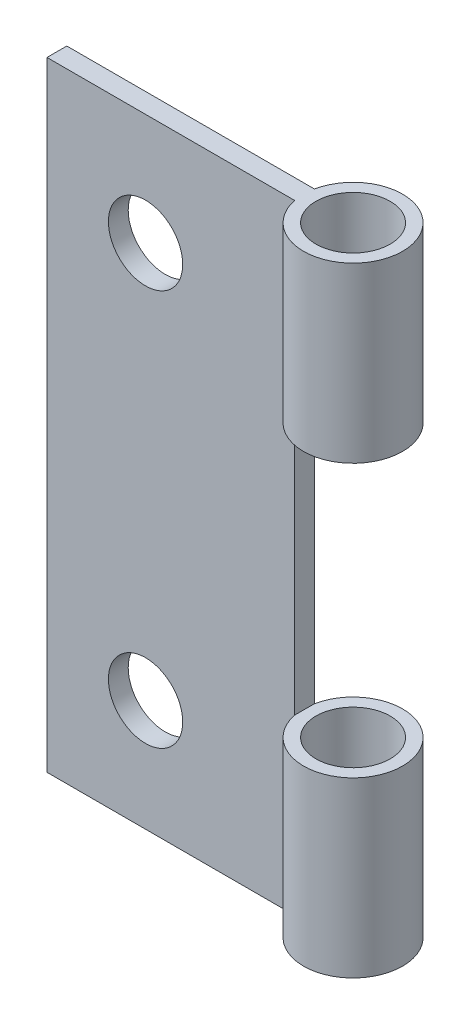
SolidWorks part; units mm, degrees
ref_plane "前视基准面" through (0, 0, 0) normal (0, 0, 1) x (1, 0, 0)
ref_plane "上视基准面" through (0, 0, 0) normal (0, 1, 0) x (1, 0, 0)
ref_plane "右视基准面" through (0, 0, 0) normal (1, 0, 0) x (0, 0, -1)
other "Configuration Table"
sketch "草图1" plane through (0, 0, 0) normal (0, 0, 1) x (1, 0, 0)
  line L1 (-5, -12.5) -> (5, -12.5)
  line L2 (-5, -12.5) -> (-5, 12.5)
  line L3 (-5, 12.5) -> (5, 12.5)
  line L4 (5, -12.5) -> (5, 12.5)
  line L5 (-5, -12.5) -> (5, 12.5) construction
  line L6 (-5, 12.5) -> (5, -12.5) construction
  point P0 (0, 0)
  point P10 (0, 0)
  dimension "D1" = 10
  dimension "D2" = 25
extrude "凸台-拉伸1" add sketch "草图1" along normal blind 0.8
sketch "草图2" plane through (0, -12.5, 0) normal (0, -1, 0) x (1, 0, 0)
  line L2 (-5, 0.358) -> (49995, 0.358) construction
  line L4 (5, 0.0347) -> (5, 50000.0347) construction
  circle A1 centre (6.9596, 0.4) radius 2
  circle A2 centre (6.9596, 0.4) radius 1.5
  dimension "D1" = 4
  dimension "D2" = 3
extrude "凸台-拉伸2" add sketch "草图2" against normal blind 7
mirror "镜向1" about plane through (0, 0, 0) normal (0, 1, 0) of "凸台-拉伸2"
sketch "草图3" plane through (0, 0, 0.8) normal (0, 0, 1) x (1, 0, 0)
  line L0 (6.9798, 12.5) -> (6.9798, 50012.5) construction
  line L1 (8.9596, 12.5) -> (5, 12.5) construction
  line L2 (-1.0202, 13.7164) -> (-1.0202, 50013.7164) construction
  line L3 (5, 12.5) -> (-5, 12.5) construction
  circle A0 centre (-1.0202, 8) radius 1.5
  circle A1 centre (-1.0202, -8) radius 1.5
  point P4 (6.9798, 12.5)
  dimension "D2" = 3
  dimension "D3" = 3
  dimension "D5" = 16
  dimension "D1" = 8
  dimension "D4" = 4.5
extrude "切除-拉伸1" cut sketch "草图3" against normal up to surface (0.8 mm away) up to face at (1.6667, 0, 0)
